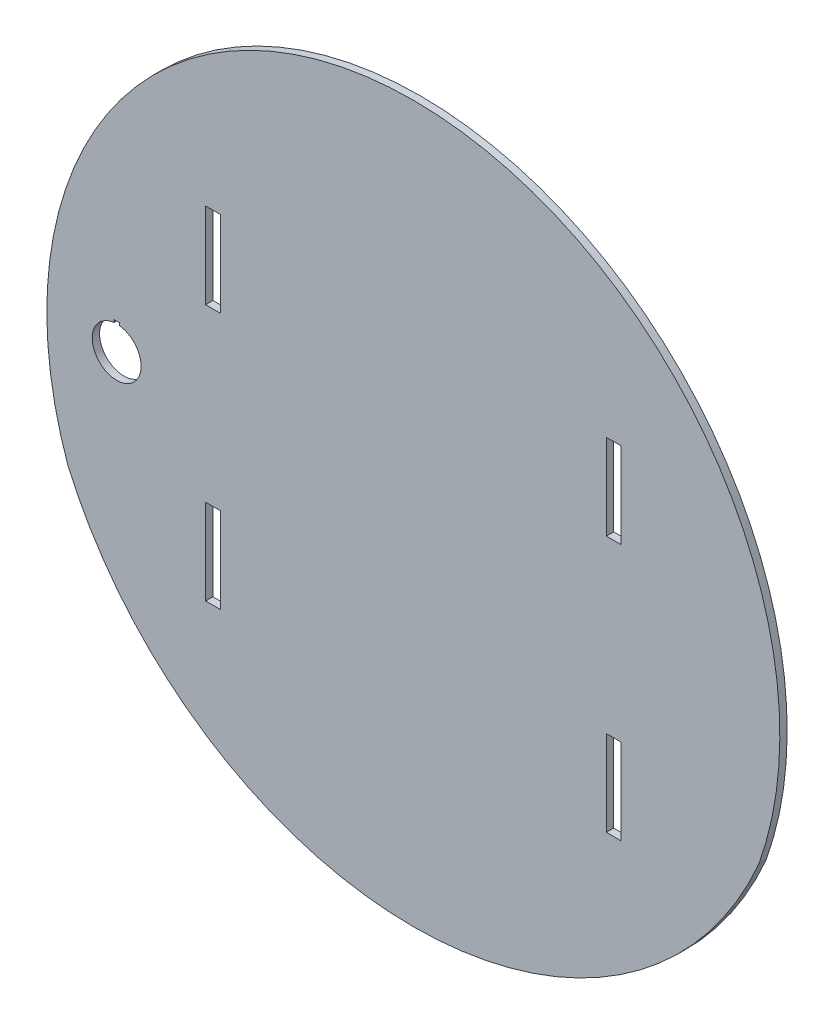
SolidWorks part; units mm, degrees
ref_plane "Plano frontal" through (0, 0, 0) normal (0, 0, 1) x (1, 0, 0)
ref_plane "Plano superior" through (0, 0, 0) normal (0, 1, 0) x (1, 0, 0)
ref_plane "Plano direito" through (0, 0, 0) normal (1, 0, 0) x (0, 0, -1)
sketch "Esboço1" plane through (0, 0, 0) normal (0, 0, 1) x (1, 0, 0)
  line L0 (0, 150) -> (0, -50) construction
  line L3 (-121.4214, 0) -> (-121.4214, 11) construction
  line L4 (-120.3214, 11) -> (-122.5214, 11)
  line L5 (-122.5214, 11) -> (-122.5214, 9.9393)
  line L6 (-120.3214, 11) -> (-120.3214, 9.9393)
  line L7 (0, 0) -> (-242.8427, 0) construction
  line L8 (-81.659, 70) -> (-20.2399, 70) construction
  line L9 (-79, -70) -> (-24.6269, -70) construction
  line L10 (-85, -70) -> (-85, -35)
  line L11 (-79, -70) -> (-79, -35)
  line L12 (-85, 70) -> (-79, 70)
  line L13 (-85, -70) -> (-79, -70)
  line L18 (-85, -35) -> (-79, -35)
  line L19 (-85, 35) -> (-79, 35)
  line L20 (-79, 35) -> (-79, 70)
  line L21 (-85, 35) -> (-85, 70)
  line L22 (85, -70) -> (79, -70)
  line L23 (85, -70) -> (85, -35)
  line L24 (85, -35) -> (79, -35)
  line L25 (79, -70) -> (79, -35)
  line L26 (85, 35) -> (85, 70)
  line L27 (85, 35) -> (79, 35)
  line L28 (79, 35) -> (79, 70)
  line L29 (85, 70) -> (79, 70)
  arc A0 (141.4214, -50) -> (-141.4214, -50) centre (0, 0) ccw
  arc A1 (-122.5214, 9.9393) -> (-120.3214, 9.9393) centre (-121.4214, 0) ccw
  arc A2 (141.4214, -50) -> (-141.4214, -50) centre (0, 11.0974) cw
  point P8 (-121.4214, -10)
  point P13 (-121.4214, 11)
  point P18 (-90, 70)
  point P21 (90, 70)
  point P22 (-150, 0)
  point P23 (-90, -70)
  point P24 (90, -70)
  point P27 (-85, 0)
  point P30 (-79, 0)
  dimension "D1" = 300
  dimension "D3" = 20
  dimension "D9" = 65
  dimension "D10" = 140
  dimension "D11" = 6
  dimension "D2" = 35
  dimension "D4" = 21
  dimension "D5" = 2.2
  dimension "D6" = 35
  dimension "D7" = 20
  dimension "D8" = 90
extrude "Ressalto-extrusão1" add sketch "Esboço1" along normal blind 3
